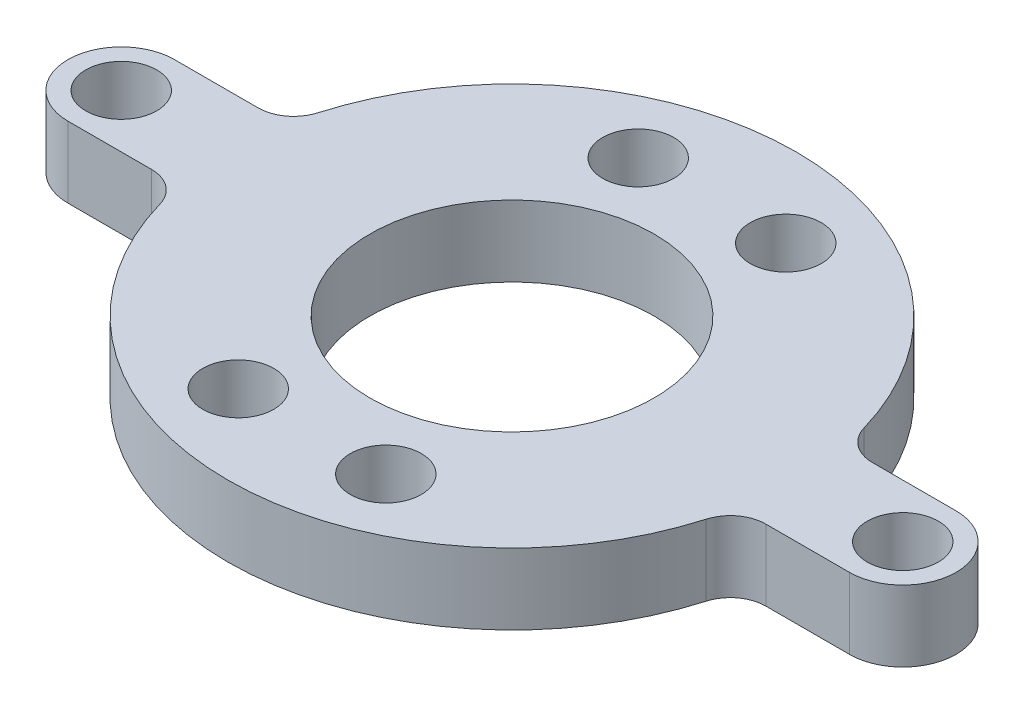
SolidWorks part; units mm, degrees
ref_plane "Front Plane" through (0, 0, 0) normal (0, 0, 1) x (1, 0, 0)
ref_plane "Top Plane" through (0, 0, 0) normal (0, 1, 0) x (1, 0, 0)
ref_plane "Right Plane" through (0, 0, 0) normal (1, 0, 0) x (0, 0, -1)
sketch "Sketch1" plane through (0, 0, 0) normal (0, 1, 0) x (1, 0, 0)
  line L0 (-351.5615, 0) -> (17226.515, 0) construction
  line L1 (0, -351.5615) -> (0, 17226.515) construction
  line L2 (-55, -7.5) -> (-43.229, -7.5)
  line L3 (55, -7.5) -> (43.229, -7.5)
  line L4 (55, 7.5) -> (43.229, 7.5)
  line L5 (-55, 7.5) -> (-43.229, 7.5)
  line L6 (0, 0) -> (0, 30) construction
  line L7 (0, 0) -> (10.3835, 28.1457) construction
  circle A0 centre (0, 0) radius 20
  circle A1 centre (0, 0) radius 30 construction
  arc A2 (-38.4258, -11.1111) -> (38.4258, -11.1111) centre (0, 0) ccw
  circle A3 centre (55, 0) radius 5
  arc A4 (55, -7.5) -> (55, 7.5) centre (55, 0) ccw
  circle A7 centre (-55, 0) radius 5
  arc A8 (-55, -7.5) -> (-55, 7.5) centre (-55, 0) cw
  circle A9 centre (10.3835, 28.1457) radius 5
  circle A10 centre (-10.3835, 28.1457) radius 5
  circle A11 centre (10.3835, -28.1457) radius 5
  circle A12 centre (-10.3835, -28.1457) radius 5
  arc A13 (-38.4258, -11.1111) -> (-43.229, -7.5) centre (-43.229, -12.5) ccw
  arc A14 (-38.4258, 11.1111) -> (-43.229, 7.5) centre (-43.229, 12.5) cw
  arc A15 (38.4258, -11.1111) -> (43.229, -7.5) centre (43.229, -12.5) cw
  arc A16 (38.4258, 11.1111) -> (43.229, 7.5) centre (43.229, 12.5) ccw
  arc A17 (38.4258, 11.1111) -> (-38.4258, 11.1111) centre (0, 0) ccw
  dimension "D2" = 40
  dimension "D3" = 60
  dimension "D4" = 80
  dimension "D5" = 10
  dimension "D6" = 15
  dimension "D8" = 10
  dimension "D9" = 10
  dimension "D1" = 20.25
  dimension "D7" = 55
extrude "Boss-Extrude2" add sketch "Sketch1" along normal blind 10
